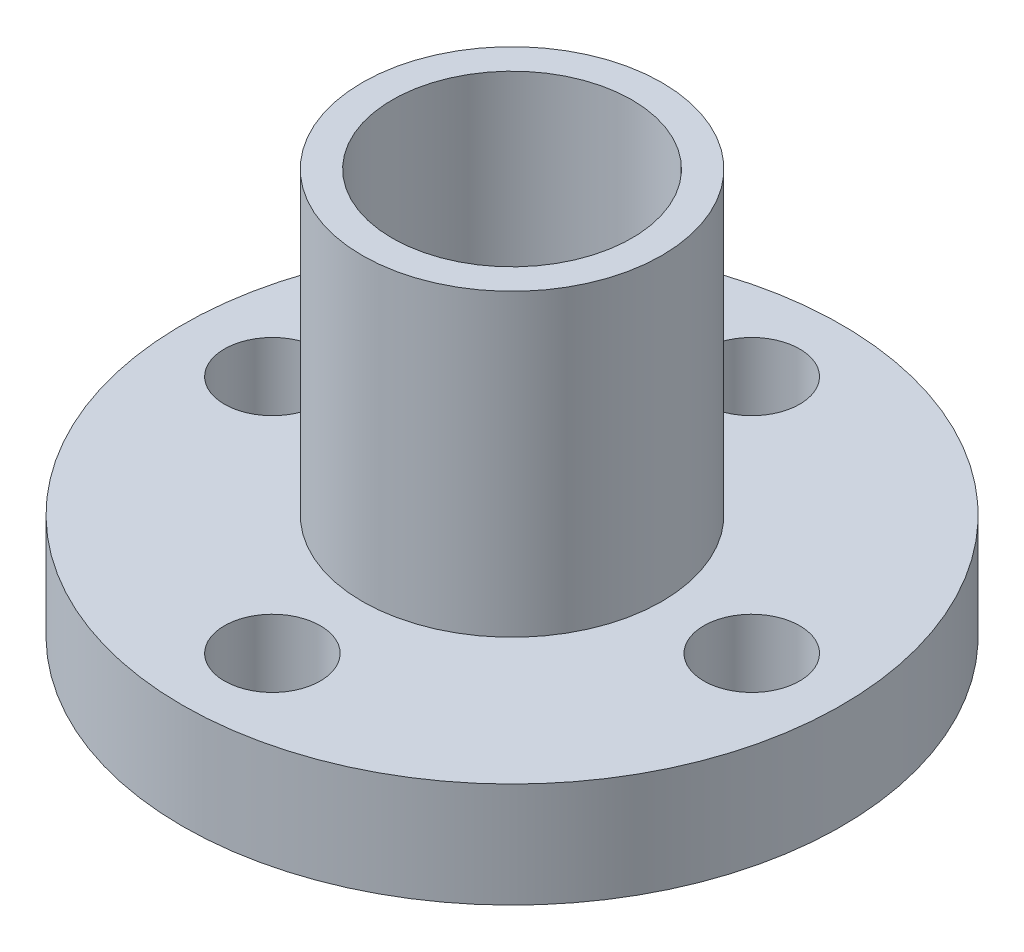
SolidWorks part; units mm, degrees
ref_plane "前视基准面" through (0, 0, 0) normal (0, 0, 1) x (1, 0, 0)
ref_plane "上视基准面" through (0, 0, 0) normal (0, 1, 0) x (1, 0, 0)
ref_plane "右视基准面" through (0, 0, 0) normal (1, 0, 0) x (0, 0, -1)
other "Configuration Table"
sketch "草图1" plane through (0, 0, 0) normal (0, 1, 0) x (1, 0, 0)
  circle A0 centre (0, 0) radius 5
  circle A1 centre (0, 0) radius 4
extrude "凸台-拉伸1" add sketch "草图1" along normal blind 15
sketch "草图2" plane through (0, 0, 0) normal (0, 1, 0) x (1, 0, 0)
  circle A0 centre (0, 0) radius 11
  circle A1 centre (0, 0) radius 5
  circle A2 centre (0, 8) radius 1.6
  circle A3 centre (0, 0) radius 8 construction
  circle A4 centre (8, 0) radius 1.6
  circle A5 centre (0, -8) radius 1.6
  circle A6 centre (-8, 0) radius 1.6
  point P16 (0, 0)
  dimension "D1" = 22
  dimension "D2" = 3.2
  dimension "D3" = 4
  dimension "D4" = 8
extrude "凸台-拉伸2" add sketch "草图2" along normal blind 3.5 from offset 1.5
